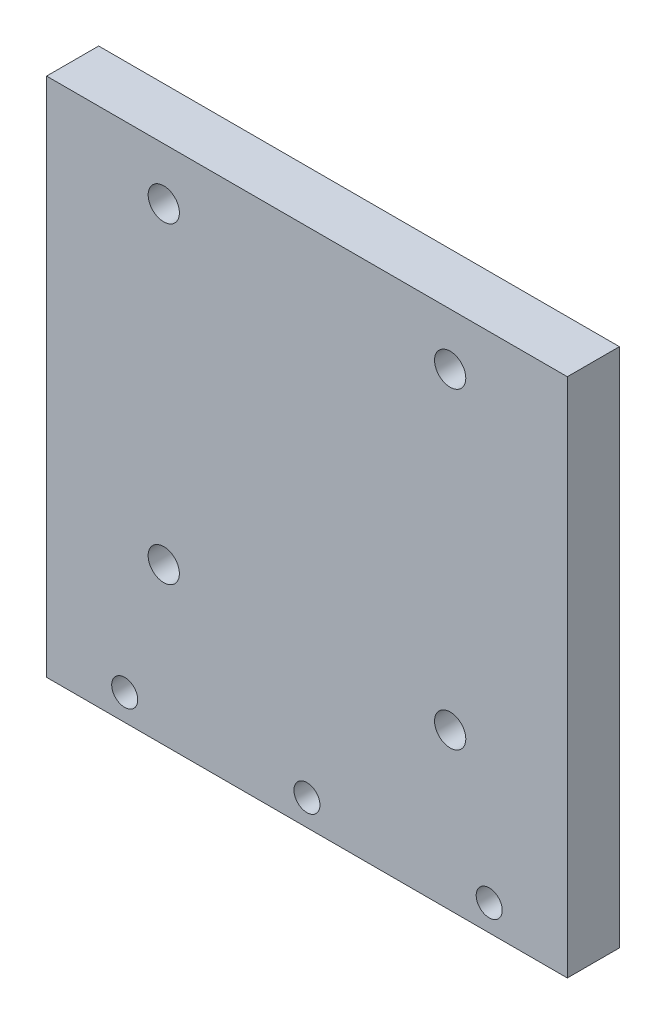
SolidWorks part; units mm, degrees
ref_plane "Front Plane" through (0, 0, 0) normal (0, 0, 1) x (1, 0, 0)
ref_plane "Top Plane" through (0, 0, 0) normal (0, 1, 0) x (1, 0, 0)
ref_plane "Right Plane" through (0, 0, 0) normal (1, 0, 0) x (0, 0, -1)
sketch "Sketch2" plane through (0, 0, 0) normal (0, 0, 1) x (1, 0, 0)
  line L0 (-50, -2.0791) -> (50, -2.0791) construction
  line L1 (-50, -42.0791) -> (50, -42.0791)
  line L2 (-50, -42.0791) -> (-50, 37.9209)
  line L3 (-50, 37.9209) -> (50, 37.9209)
  line L4 (50, -42.0791) -> (50, 37.9209)
  line L7 (50, 27.9209) -> (-50, 27.9209) construction
  circle A0 centre (27.5, 27.9209) radius 3
  circle A1 centre (-27.5, 27.9209) radius 3
  circle A2 centre (-27.5, -32.0791) radius 3
  circle A3 centre (27.5, -32.0791) radius 3
  point P0 (0, 0)
  dimension "D4" = 6
  dimension "D1" = 80
  dimension "D2" = 100
  dimension "D5" = 22.5
  dimension "D6" = 60
  dimension "D3" = 2
extrude "Boss-Extrude1" add sketch "Sketch2" along normal blind 10
sketch "Sketch3" plane through (0, -42.0791, 0) normal (0, -1, 0) x (1, 0, 0)
  line L1 (-50, 10) -> (50, 10)
  line L2 (-50, 10) -> (-50, 0)
  line L3 (-50, 0) -> (50, 0)
  line L4 (50, 10) -> (50, 0)
extrude "Boss-Extrude2" add sketch "Sketch3" along normal blind 20
sketch "Sketch4" plane through (0, 0, 10) normal (0, 0, 1) x (1, 0, 0)
  line L0 (-50, -57.0791) -> (50, -57.0791) construction
  line L1 (50, -62.0791) -> (50, 37.9209) construction
  line L2 (50, -62.0791) -> (-50, -62.0791) construction
  line L3 (0, 0) -> (0, -62.0791) construction
  line L4 (-50, 37.9209) -> (-50, -62.0791) construction
  circle A0 centre (0, -57.0791) radius 2.5
  circle A1 centre (-35, -57.0791) radius 2.5
  circle A2 centre (35, -57.0791) radius 2.5
  point P15 (0, 0)
  dimension "D4" = 5
  dimension "D1" = 5
  dimension "D2" = 15
  dimension "D3" = 15
extrude "Cut-Extrude1" cut sketch "Sketch4" against normal up to next
